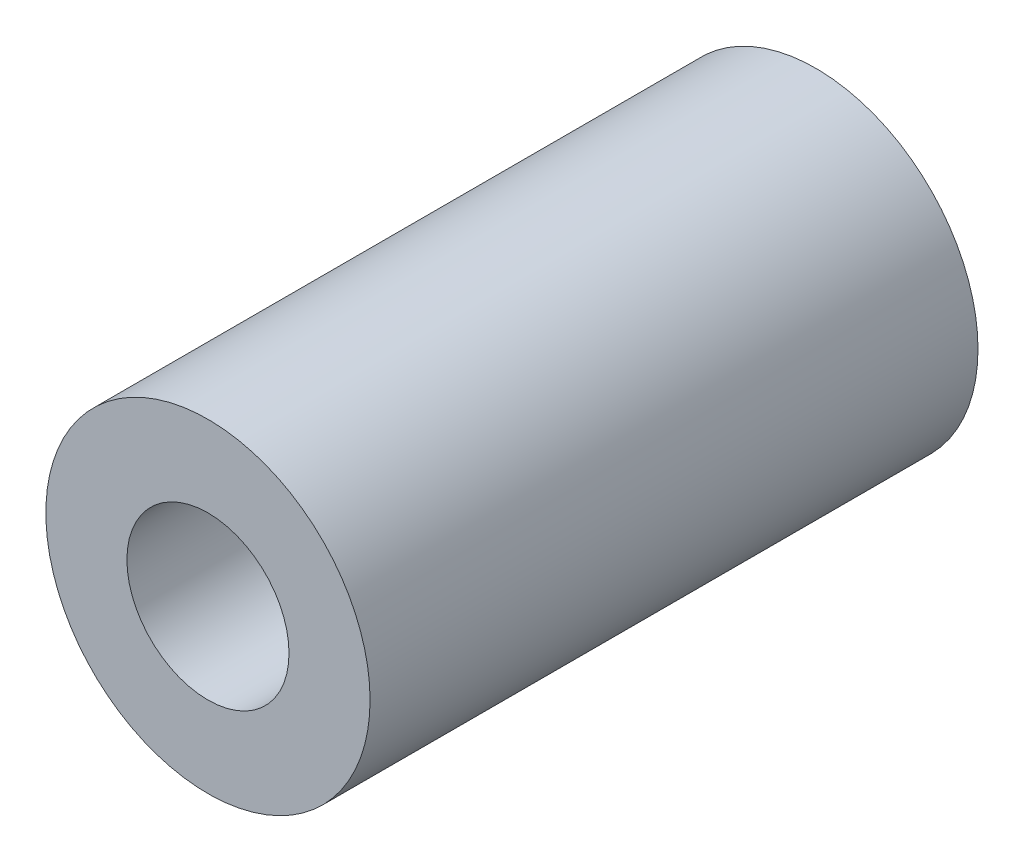
SolidWorks part; units mm, degrees
ref_plane "Front Plane" through (0, 0, 0) normal (0, 0, 1) x (1, 0, 0)
ref_plane "Top Plane" through (0, 0, 0) normal (0, 1, 0) x (1, 0, 0)
ref_plane "Right Plane" through (0, 0, 0) normal (1, 0, 0) x (0, 0, -1)
sketch "Sketch1" plane through (0, 0, 0) normal (0, 0, 1) x (1, 0, 0)
  circle A0 centre (0, 0) radius 2.5
  arc A1 (1.5, -2) -> (-1.5, -2) centre (0, 0) ccw construction
  circle A2 centre (0, 0) radius 8
  dimension "D1" = 16
extrude "Boss-Extrude1" add sketch "Sketch1" against normal blind 15
sketch "Sketch3" plane through (0, 0, 0) normal (0, 0, 1) x (1, 0, 0)
  circle A0 centre (0, 0) radius 8 construction
  circle A1 centre (0, 0) radius 8
  circle A2 centre (0, 0) radius 4
  dimension "D1" = 8
extrude "Boss-Extrude2" add sketch "Sketch3" along normal blind 15
